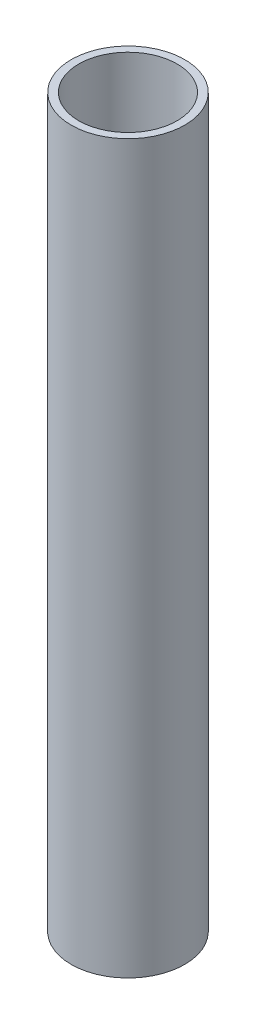
SolidWorks part; units mm, degrees
ref_plane "Front Plane" through (0, 0, 0) normal (0, 0, 1) x (1, 0, 0)
ref_plane "Top Plane" through (0, 0, 0) normal (0, 1, 0) x (1, 0, 0)
ref_plane "Right Plane" through (0, 0, 0) normal (1, 0, 0) x (0, 0, -1)
sketch "Sketch1" plane through (0, 0, 0) normal (0, 1, 0) x (1, 0, 0)
  circle A0 centre (0, 0) radius 7.5
  circle A1 centre (0, 0) radius 6.5
  dimension "D1" = 15
  dimension "D2" = 13
extrude "Boss-Extrude1" add sketch "Sketch1" along normal blind 96
